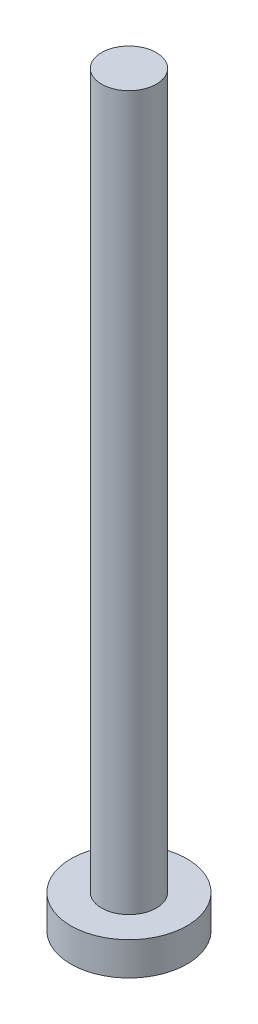
SolidWorks part; units mm, degrees
ref_plane "Front Plane" through (0, 0, 0) normal (0, 0, 1) x (1, 0, 0)
ref_plane "Top Plane" through (0, 0, 0) normal (0, 1, 0) x (1, 0, 0)
ref_plane "Right Plane" through (0, 0, 0) normal (1, 0, 0) x (0, 0, -1)
sketch "Sketch1" plane through (0, 0, 0) normal (0, 1, 0) x (1, 0, 0)
  circle A0 centre (0, 0) radius 7
  dimension "D1" = 14
extrude "Boss-Extrude1" add sketch "Sketch1" along normal blind 4
sketch "Sketch2" plane through (0, 4, 0) normal (0, 1, 0) x (1, 0, 0)
  circle A0 centre (0, 0) radius 3.3
  dimension "D1" = 6.6
extrude "Boss-Extrude2" add sketch "Sketch2" along normal blind 86
